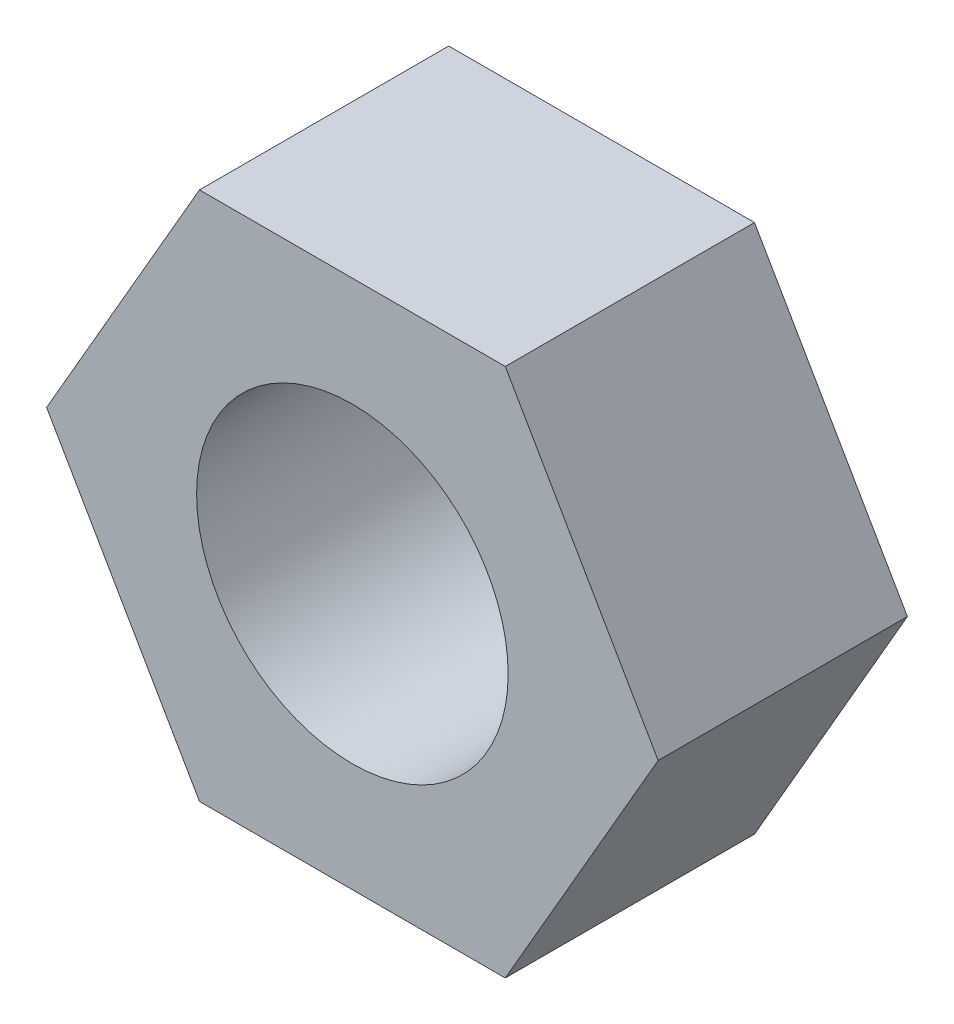
SolidWorks part; units mm, degrees
material "Galvanized Steel"
ref_plane "Front Plane" through (0, 0, 0) normal (0, 0, 1) x (1, 0, 0)
ref_plane "Top Plane" through (0, 0, 0) normal (0, 1, 0) x (1, 0, 0)
ref_plane "Right Plane" through (0, 0, 0) normal (1, 0, 0) x (0, 0, -1)
sketch "Sketch1" plane through (0, 0, 0) normal (0, 0, 1) x (1, 0, 0)
  line L1 (-9.815, 0) -> (-4.9075, -8.5)
  line L2 (-4.9075, -8.5) -> (4.9075, -8.5)
  line L3 (4.9075, -8.5) -> (9.815, 0)
  line L4 (9.815, 0) -> (4.9075, 8.5)
  line L5 (4.9075, 8.5) -> (-4.9075, 8.5)
  line L6 (-4.9075, 8.5) -> (-9.815, 0)
  circle A0 centre (0, 0) radius 8.5 construction
  dimension "D1" = 17
extrude "Boss-Extrude1" add sketch "Sketch1" along normal blind 8
sketch "Sketch2" plane through (0, 0, 8) normal (0, 0, 1) x (1, 0, 0)
  circle A0 centre (0, 0) radius 5
  dimension "D1" = 10
extrude "Cut-Extrude1" cut sketch "Sketch2" against normal blind 10
